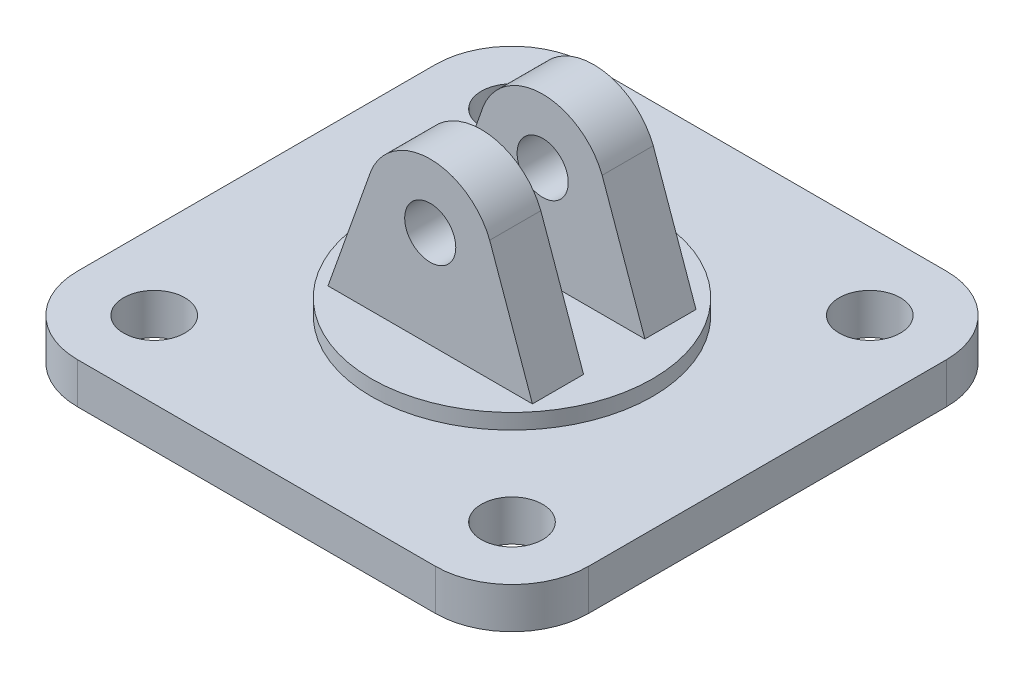
SolidWorks part; units mm, degrees
ref_plane "前基準面" through (0, 0, 0) normal (0, 0, 1) x (1, 0, 0)
ref_plane "上基準面" through (0, 0, 0) normal (0, 1, 0) x (1, 0, 0)
ref_plane "右基準面" through (0, 0, 0) normal (1, 0, 0) x (0, 0, -1)
sketch "草圖3" plane through (0, 0, 0) normal (0, 1, 0) x (1, 0, 0)
  line L1 (0, 0) -> (0, 50) construction
  line L3 (35, 50) -> (-35, 50)
  line L4 (50, 35) -> (50, -35)
  line L5 (35, -50) -> (-35, -50)
  line L6 (-50, 35) -> (-50, -35)
  arc A0 (50, -35) -> (35, -50) centre (35, -35) cw
  arc A1 (-35, -50) -> (-50, -35) centre (-35, -35) cw
  arc A2 (-35, 50) -> (-50, 35) centre (-35, 35) ccw
  arc A3 (35, 50) -> (50, 35) centre (35, 35) cw
  point P9 (50, -50)
  point P12 (-50, -50)
  point P15 (-50, 50)
  dimension "D4" = 15
  dimension "D1" = 50
  dimension "D2" = 50
  dimension "D3" = 100
  dimension "D5" = 100
extrude "填料-伸長3" add sketch "草圖3" along normal blind 8
sketch "草圖4" plane through (0, 8, 0) normal (0, 1, 0) x (1, 0, 0)
  circle A0 centre (0, 0) radius 27.5
  dimension "D1" = 55
extrude "填料-伸長4" add sketch "草圖4" along normal blind 3
sketch "草圖6" plane through (0, 8, 0) normal (0, 1, 0) x (1, 0, 0)
  line L0 (35, 50) -> (-35, 50) construction
  line L1 (-50, 35) -> (-50, -35) construction
  circle A0 centre (-35, 35) radius 6
  dimension "D1" = 12
  dimension "D2" = 15
  dimension "D3" = 15
extrude "除料-伸長1" cut sketch "草圖6" against normal through all contours A0
pattern_linear "直線複製排列1" count 2 spacing 70 along (1, 0, 0) count 2 spacing 70 along (0, 0, 1) of "除料-伸長1"
sketch "草圖9" plane through (0, 0, 0) normal (0, -1, 0) x (1, 0, 0)
  line L1 (-20, -25) -> (20, -25)
  line L2 (-25, -20) -> (-25, 20)
  line L3 (-20, 25) -> (20, 25)
  line L4 (25, -20) -> (25, 20)
  arc A0 (-25, 20) -> (-20, 25) centre (-20, 20) cw
  arc A1 (-20, -25) -> (-25, -20) centre (-20, -20) cw
  arc A2 (20, -25) -> (25, -20) centre (20, -20) ccw
  arc A3 (20, 25) -> (25, 20) centre (20, 20) cw
  point P7 (-25, 25)
  point P12 (25, -25)
  point P15 (25, 25)
  dimension "D5" = 5
  dimension "D1" = 25
  dimension "D2" = 25
  dimension "D3" = 50
  dimension "D4" = 50
extrude "除料-伸長2" cut sketch "草圖9" against normal blind 2
sketch "草圖13" plane through (0, 0, 0) normal (0, 0, 1) x (1, 0, 0)
  line L0 (0, 0) -> (0, 30) construction
  line L1 (-20, 11) -> (20, 11)
  line L2 (27.5, 11) -> (-27.5, 11) construction
  line L3 (-20, 11) -> (-11.6385, 34.5602)
  line L5 (11.6385, 34.5602) -> (20, 11)
  arc A1 (11.6385, 34.5602) -> (-11.6385, 34.5602) centre (0, 30) ccw
  circle A2 centre (0, 30) radius 5
  dimension "D6" = 10
  dimension "D4" = 12.5
  dimension "D1" = 30
  dimension "D2" = 40
  dimension "D3" = 7.5
  dimension "D5" = 25
extrude "填料-伸長6" add sketch "草圖13" along normal mid plane 32
sketch "草圖14" plane through (0, 0, 0) normal (0, 0, 1) x (1, 0, 0)
  line L2 (-20, 11) -> (20, 11)
  line L3 (-20, 11) -> (-20, 46)
  line L4 (-20, 46) -> (20, 46)
  line L5 (20, 11) -> (20, 46)
  dimension "D1" = 40
  dimension "D2" = 35
extrude "除料-伸長3" cut sketch "草圖14" against normal mid plane 12
